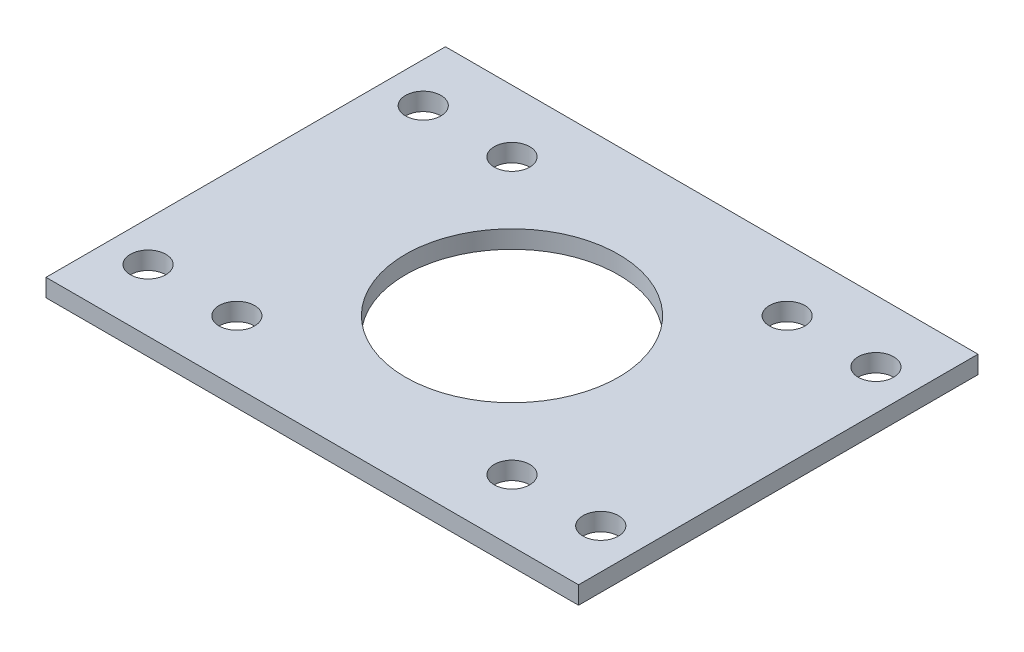
SolidWorks part; units mm, degrees
ref_plane "Front Plane" through (0, 0, 0) normal (0, 0, 1) x (1, 0, 0)
ref_plane "Top Plane" through (0, 0, 0) normal (0, 1, 0) x (1, 0, 0)
ref_plane "Right Plane" through (0, 0, 0) normal (1, 0, 0) x (0, 0, -1)
sketch "Sketch1" plane through (0, 0, 0) normal (0, 1, 0) x (1, 0, 0)
  line L1 (-30, 22.5) -> (30, 22.5)
  line L2 (-30, 22.5) -> (-30, -22.5)
  line L3 (-30, -22.5) -> (30, -22.5)
  line L4 (30, 22.5) -> (30, -22.5)
  line L5 (-30, 22.5) -> (30, -22.5) construction
  line L6 (-30, -22.5) -> (30, 22.5) construction
  circle A0 centre (-15.5, 15.5) radius 2
  circle A1 centre (15.5, 15.5) radius 2
  circle A2 centre (15.5, -15.5) radius 2
  circle A3 centre (-15.5, -15.5) radius 2
  circle A4 centre (-25.5, 15.5) radius 2
  circle A5 centre (-25.5, -15.5) radius 2
  circle A6 centre (25.5, -15.5) radius 2
  circle A7 centre (25.5, 15.5) radius 2
  point P0 (0, 0)
  point P11 (0, 0)
  dimension "D3" = 4
  dimension "D4" = 4
  dimension "D5" = 10
  dimension "D1" = 31
  dimension "D2" = 31
  dimension "D6" = 10
  dimension "D7" = 10
  dimension "D8" = 10
  dimension "D9" = 60
  dimension "D10" = 45
extrude "Boss-Extrude1" add sketch "Sketch1" along normal blind 2
sketch "Sketch2" plane through (0, 2, 0) normal (0, 1, 0) x (1, 0, 0)
  circle A0 centre (0, 0) radius 12
  dimension "D1" = 24
extrude "Cut-Extrude1" cut sketch "Sketch2" against normal through all
